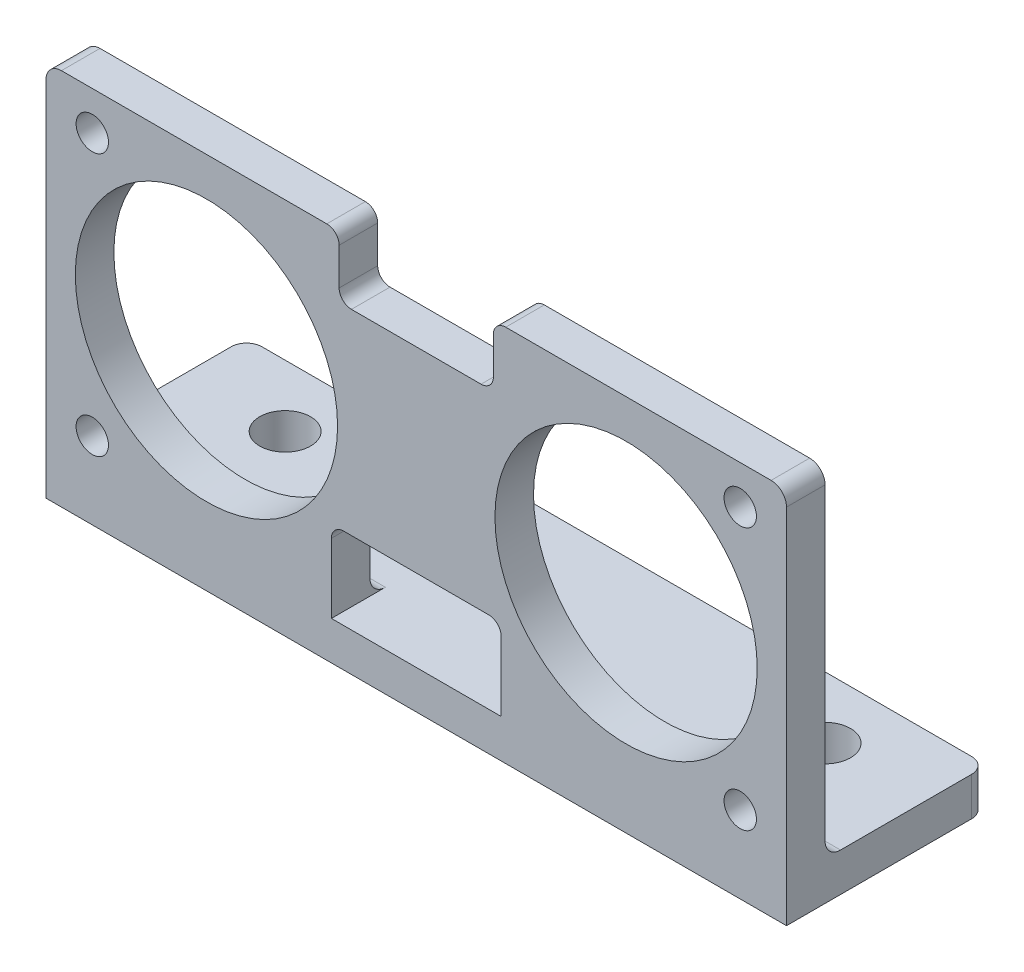
SolidWorks part; units mm, degrees
ref_plane "前视基准面" through (0, 0, 0) normal (0, 0, 1) x (1, 0, 0)
ref_plane "上视基准面" through (0, 0, 0) normal (0, 1, 0) x (1, 0, 0)
ref_plane "右视基准面" through (0, 0, 0) normal (1, 0, 0) x (0, 0, -1)
other "Configuration Table"
sketch "草图1" plane through (0, 0, 0) normal (0, 0, 1) x (1, 0, 0)
  line L0 (-13.6, 0) -> (13.6, 0) construction
  line L1 (-24, -11) -> (24, -11)
  line L2 (-24, -11) -> (-24, 11)
  line L3 (-24, 11) -> (24, 11)
  line L4 (24, -11) -> (24, 11)
  line L5 (-24, -11) -> (24, 11) construction
  line L6 (-24, 11) -> (24, -11) construction
  line L7 (-21, -8.5) -> (21, -8.5) construction
  line L8 (-21, -8.5) -> (-21, 8.5) construction
  line L9 (-21, 8.5) -> (21, 8.5) construction
  line L10 (21, -8.5) -> (21, 8.5) construction
  line L11 (-21, -8.5) -> (21, 8.5) construction
  line L12 (-21, 8.5) -> (21, -8.5) construction
  line L14 (-5.5, -5.7) -> (5.5, -5.7)
  line L15 (-5.5, -5.7) -> (-5.5, -11)
  line L16 (-5.5, -11) -> (5.5, -11)
  line L17 (5.5, -5.7) -> (5.5, -11)
  line L18 (-5.5, -5.7) -> (5.5, -11) construction
  line L19 (-5.5, -11) -> (5.5, -5.7) construction
  line L20 (-5, 7) -> (5, 7)
  line L21 (-5, 7) -> (-5, 11)
  line L22 (-5, 11) -> (5, 11)
  line L23 (5, 7) -> (5, 11)
  line L24 (-5, 7) -> (5, 11) construction
  line L25 (-5, 11) -> (5, 7) construction
  circle A1 centre (13.6, 0) radius 8.5
  circle A2 centre (-13.6, 0) radius 8.5
  circle A3 centre (-21, 8.5) radius 1.05
  circle A4 centre (21, 8.5) radius 1.05
  circle A5 centre (21, -8.5) radius 1.05
  circle A6 centre (-21, -8.5) radius 1.05
  point P0 (0, 0)
  point P6 (0, 0)
  point P14 (0, 0)
  point P16 (0, -8.35)
  point P22 (0, 9)
  dimension "D5" = 17
  dimension "D6" = 10
  dimension "D11" = 2.1
  dimension "D1" = 48
  dimension "D2" = 22
  dimension "D3" = 42
  dimension "D4" = 17
  dimension "D7" = 27.2
  dimension "D8" = 11
  dimension "D9" = 5.3
  dimension "D10" = 4
extrude "凸台-拉伸1" add sketch "草图1" along normal blind 2.5 contours L14 L17 L1 L4 L3 L2 L15 A2 A1
fillet "圆角1" radius 0.8 6 edges at (-5.5, -5.7, 1.25) (5.5, -5.7, 1.25) (-5, 11, 1.25) (5, 11, 1.25) (5, 7, 1.25) (-5, 7, 1.25)
sketch "草图2" plane through (0, -11, 0) normal (0, -1, 0) x (1, 0, 0)
  line L0 (24, 2.5) -> (24, 0) construction
  line L1 (-24, 2.5) -> (24, 2.5)
  line L2 (-24, 2.5) -> (-24, -10.5)
  line L3 (-24, -10.5) -> (24, -10.5)
  line L4 (24, 2.5) -> (24, -10.5)
  line L5 (-24, -6.5) -> (24, -6.5) construction
  line L6 (0, 0) -> (0, -10.5) construction
  line L7 (-4.7, 0) -> (4.7, 0) construction
  circle A0 centre (-17.5, -6.5) radius 1.65
  circle A1 centre (17.5, -6.5) radius 1.65
  point P17 (-17.4345, -7.5)
  dimension "D2" = 35
  dimension "D3" = 3.3
  dimension "D4" = 3.3
  dimension "D1" = 13
  dimension "D5" = 4
  dimension "D6" = 35
extrude "凸台-拉伸2" add sketch "草图2" along normal blind 2.5
fillet "圆角2" radius 1 2 edges at (-14.75, -11, 0) (14.75, -11, 0)
fillet "圆角3" radius 1 4 edges at (24, -12.25, -10.5) (-24, -12.25, -10.5) (24, 11, 1.25) (-24, 11, 1.25)
